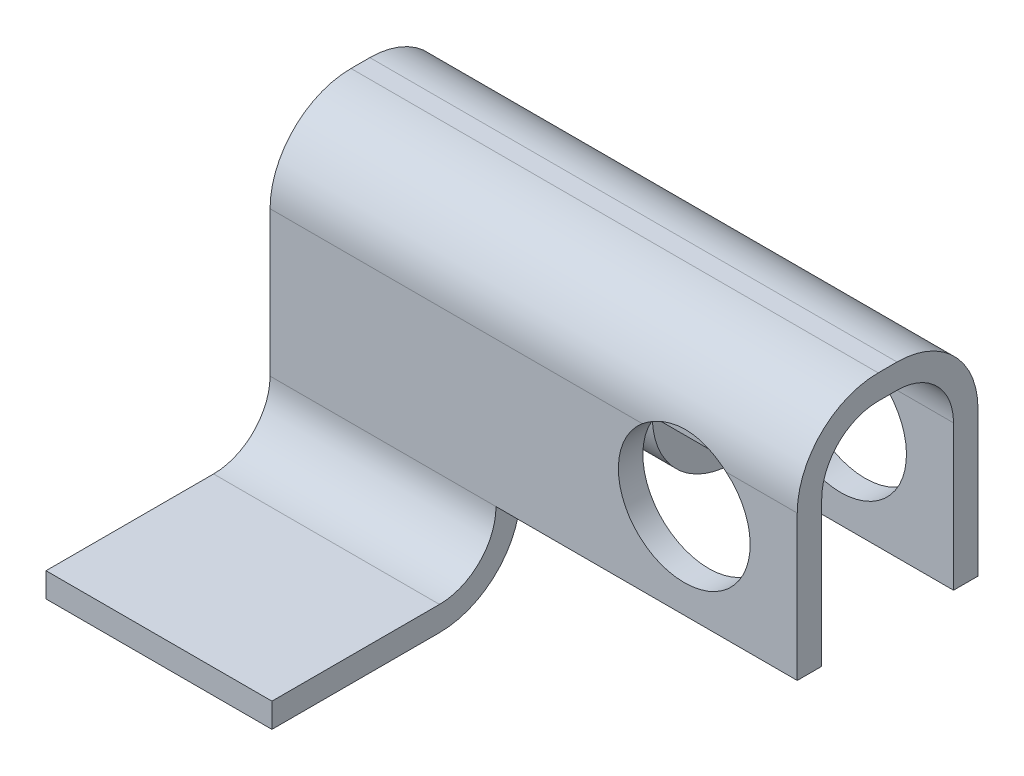
SolidWorks part; units mm, degrees
ref_plane "前视基准面" through (0, 0, 0) normal (0, 0, 1) x (1, 0, 0)
ref_plane "上视基准面" through (0, 0, 0) normal (0, 1, 0) x (1, 0, 0)
ref_plane "右视基准面" through (0, 0, 0) normal (1, 0, 0) x (0, 0, -1)
sketch "草图1" plane through (0, 0, 0) normal (1, 0, 0) x (0, 0, -1)
  line L0 (-16.7, 0) -> (-3.5, 0)
  line L1 (-3.5, 0) -> (-3.5, 15)
  line L2 (0, 0) -> (0, 26.6711) construction
  line L3 (3.5, 0) -> (3.5, 15)
  line L4 (16.7, 0) -> (3.5, 0)
  line L5 (-3.5, 15) -> (3.5, 15)
  dimension "D1" = 33.4
  dimension "D2" = 7
  dimension "D3" = 15
extrude "拉伸-薄壁1" add sketch "草图1" along normal mid plane 28 thin thin type one direction wall 1.3
sketch "草图3" plane through (0, 1.3, 0) normal (0, 1, 0) x (1, 0, 0)
  line L0 (14, 16.7) -> (-14, 16.7) construction
  line L1 (14, -16.7) -> (-2, -16.7)
  line L2 (14, -16.7) -> (14, 16.7)
  line L3 (14, 16.7) -> (-2, 16.7)
  line L4 (-2, -16.7) -> (-2, 16.7)
  line L5 (14, -16.7) -> (-2, 16.7) construction
  line L6 (14, 16.7) -> (-2, -16.7) construction
  point P0 (6, 0)
  dimension "D1" = 2
extrude "切除-拉伸1" cut sketch "草图3" against normal through all from offset 3
hole_wizard "Ø7.0 (7) 直径孔1" positions "草图5" profile "草图4" hole size "Ø7.0" standard "GB" end condition through all
sketch "草图5" plane through (0, 0, 4.8) normal (0, 0, 1) x (1, 0, 0)
  line L0 (14, 12) -> (14, 4.3) construction
  line L1 (14, 16.3) -> (-14, 16.3) construction
  point P0 (8, 9.3)
  point P10 (10.8561, 8.0865)
  dimension "D1" = 6
  dimension "D2" = 7
sketch "草图4" plane through (8, 9.3, 4.8) normal (1, 0, 0) x (0, -1, 0)
  line L0 (0, 0) -> (0, 21.5)
  line L1 (0, 21.5) -> (3.5, 21.5)
  line L2 (3.5, 21.5) -> (3.5, 0)
  line L5 (3.5, 0) -> (0, 0)
  line L11 (0, -6.35) -> (0, 107.95) construction
  dimension "通孔孔直径" = 7
  dimension "通孔孔深度" = 21.5
